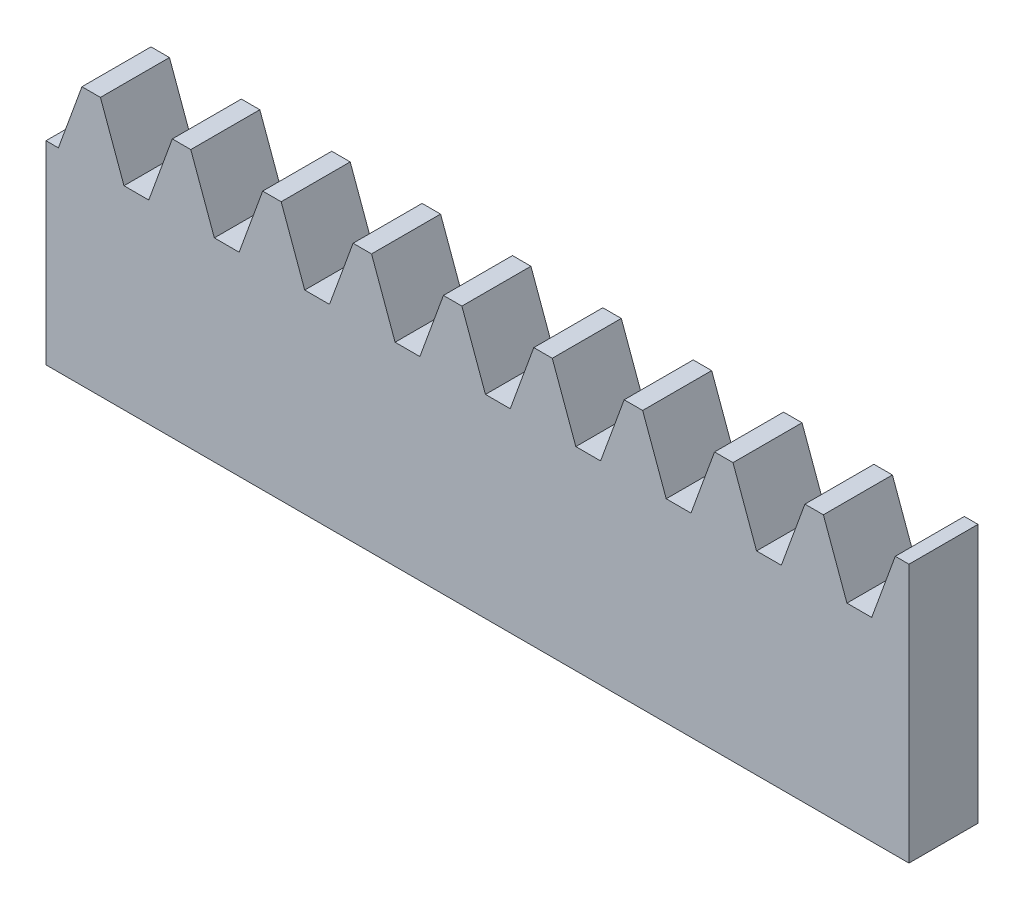
SolidWorks part; units mm, degrees
extrude "Blank" add sketch "BlankSke" against normal blind 12
sketch "BlankSke" plane through (0, 0, 0) normal (0, 0, 1) x (1, 0, 0)
  line L1 (0, 0) -> (150, 0)
  line L2 (0, 0) -> (0, 45)
  line L3 (0, 45) -> (150, 45)
  line L4 (150, 0) -> (150, 45)
  dimension "Length" = 150
  dimension "Blank_height" = 45
ref_plane "Plane1" through (0, 0, 0) normal (0, 0, 1) x (1, 0, 0)
ref_plane "Plane2" through (0, 0, 0) normal (0, 1, 0) x (1, 0, 0)
ref_plane "Plane3" through (0, 0, 0) normal (1, 0, 0) x (0, 0, -1)
other "Configuration Table"
sketch "HoldingSke" plane through (0, 0, 0) normal (0, 1, 0) x (1, 0, 0)
  line L0 (0, 0) -> (0.0278, 0.1981)
  line L1 (-15, 0) -> (100, 0) construction
  line L2 (0, 0) -> (-2.1039, 2.3779)
  line L3 (0, 0) -> (-11.863, 4.5341)
  line L4 (0, 0) -> (8.4773, 1.6478)
  line L5 (0, 0) -> (-23.7986, -8.8762)
  line L6 (0, 0) -> (-10.5278, -7.1032)
  line L9 (-71.009, 38.7566) -> (69.9449, 90.0596)
  line L10 (-76.2, 7.3779) -> (-36.2, 7.3779)
  line L11 (0, 0) -> (-12, 0)
  line L12 (-76.2, 101.6) -> (-76.033, 101.6)
  line L13 (24.9733, 27.94) -> (52.9518, 28.4284)
  line L14 (24.9733, 27.94) -> (24.9743, 27.94)
  line L15 (24.9733, 27.94) -> (100.4006, 29.5858)
  circle A0 centre (0, 0) radius 19.05
  circle A1 centre (0, 0) radius 20
  circle A2 centre (0, 0) radius 12.7
  dimension "MPH" = 40
  dimension "Diameter" = 38.1
  dimension "Num_teeth" = 11
  dimension "Pitch" = 0.2
  dimension "Show_teeth" = 998
  dimension "Thickness" = 12.7
  dimension "Ap" = 20
  dimension "Pitch_height" = 40
  dimension "Width" = 12
  dimension "Backlash" = 0.167
  dimension "Addendum_fac" = 1
  dimension "Dedendum_fac" = 1.25
  dimension "Clearance_fac" = 0.25
  dimension "Dedendum_add" = 0.001
  dimension "Length" = 150
  dimension "Module" = 5
sketch "TooCutSkeIll" plane through (0, 0, 0) normal (0, 0, 1) x (1, 0, 0)
  line L0 (-6.1999, 44.8684) -> (-2.4528, 34.5731)
  line L1 (-1.2772, 33.75) -> (1.2772, 33.75)
  line L2 (2.4528, 34.5731) -> (6.1999, 44.8684)
  line L3 (150, 45) -> (0, 45) construction
  line L4 (0, 0) -> (0, 64.897) construction
  line L5 (-13.208, 40) -> (12.954, 40) construction
  line L6 (0, 0) -> (150, 0) construction
  line L7 (4.428, 40) -> (4.428, 48.7463) construction
  line L8 (-4.428, 40) -> (-4.428, 48.7463) construction
  line L9 (6.3879, 45) -> (6.3879, 45.0254)
  line L10 (-6.3879, 45) -> (-6.3879, 45.0254)
  line L11 (-6.3879, 45.0254) -> (6.3879, 45.0254)
  arc A0 (1.2772, 33.75) -> (2.4528, 34.5731) centre (1.2772, 35.001) ccw
  arc A1 (-2.4528, 34.5731) -> (-1.2772, 33.75) centre (-1.2772, 35.001) ccw
  arc A2 (6.3879, 45) -> (6.1999, 44.8684) centre (6.3879, 44.8) ccw
  arc A3 (-6.1999, 44.8684) -> (-6.3879, 45) centre (-6.3879, 44.8) ccw
  dimension "Pitch_height" = 40
  dimension "Addendum_plus" = 5.0254
  dimension "Pressure_angle" = 20
  dimension "Gap_width" = 8.856
  dimension "Dedendum" = 6.25
extrude "ToothCutIll" [suppressed] cut sketch "TooCutSkeIll" against normal through all
sketch "TooCutSkeSim" plane through (0, 0, 0) normal (0, 0, 1) x (1, 0, 0)
  line L0 (2.1532, 33.75) -> (-2.1532, 33.75)
  line L1 (6.2571, 45.0254) -> (2.1532, 33.75)
  line L2 (0, 17.4625) -> (0, 53.467) construction
  line L3 (6.2571, 45.0254) -> (-6.2571, 45.0254)
  line L6 (-6.2571, 45.0254) -> (-2.1532, 33.75)
  line L9 (-4.428, 40) -> (4.428, 40) construction
  line L10 (0, 0) -> (150, 0) construction
  line L11 (4.428, 40) -> (4.428, 53.467) construction
  line L12 (-4.428, 40) -> (-4.428, 53.467) construction
  dimension "Pitch_height" = 40
  dimension "Addendum_plus" = 5.0254
  dimension "Pressure_angle" = 20
  dimension "Gap_width" = 8.856
  dimension "Dedendum" = 6.25
extrude "ToothCutSim" cut sketch "TooCutSkeSim" against normal through all
pattern_linear "TeethCuts" count 10 spacing 15.708 along (1, 0, 0) of "ToothCutIll", "ToothCutSim"
equation "' \"Module@HoldingSke\" = 6.35"
equation "' \"Num_teeth@HoldingSke\" = 12"
equation "' \"Ap@HoldingSke\" =  20"
equation "' \"Ap@HoldingSke\" = 20"
equation "' \"Width@HoldingSke\" = 0.25 * 25.4"
equation "' \"Show_teeth@HoldingSke\" = 500"
equation "' \"Backlash@HoldingSke\" = 0.009 * 25.4"
equation "' \"Addendum_fac@HoldingSke\" = 1.0"
equation "' \"Dedendum_fac@HoldingSke\" = 1.25"
equation "' \"Dedendum_add@HoldingSke\" = 0.00005 * 25.4"
equation "' \"Clearance_fac@HoldingSke\" = 0.25"
equation "' \"Pitch_height@HoldingSke\" = 1 * 25.4"
equation "' \"Length@HoldingSke\" = 4.71 * 25.4"
equation "\"Pitch@HoldingSke\" = 1 / \"Module@HoldingSke\""
equation "\"MPH@HoldingSke\" = \"Dedendum_fac@HoldingSke\" / \"Pitch@HoldingSke\" + 2 * \"Dedendum_add@HoldingSke\" + 0.002 * 25.4"
equation "\"MPH@HoldingSke\" = ((sgn( \"MPH@HoldingSke\" - \"Pitch_height@HoldingSke\")+1)*( \"MPH@HoldingSke\" - \"Pitch_height@HoldingSke\"))/2 + \"Pitch_height@HoldingSke\""
equation "\"Blank_height@BlankSke\" = \"Pitch_height@HoldingSke\" + \"Addendum_fac@HoldingSke\"  / \"Pitch@HoldingSke\" "
equation "\"Length@BlankSke\" =  \"Length@HoldingSke\""
equation "\"Face_width@Blank\" = \"Width@HoldingSke\""
equation "\"Pressure_angle@TooCutSkeIll\" = \"Ap@HoldingSke\""
equation "\"Addendum_plus@TooCutSkeIll\" =  \"Addendum_fac@HoldingSke\"  / \"Pitch@HoldingSke\" + 0.001 *25.4"
equation "\"Dedendum@TooCutSkeIll\" = \"Dedendum_fac@HoldingSke\"  / \"Pitch@HoldingSke\""
equation "\"Pitch_height@TooCutSkeIll\" =  \"MPH@HoldingSke\""
equation "\"Gap_width@TooCutSkeIll\" = 3.14159265 / 2 / \"Pitch@HoldingSke\" + 6 * \"Backlash@HoldingSke\""
equation "\"Pressure_angle@TooCutSkeSim\" = \"Ap@HoldingSke\""
equation "\"Addendum_plus@TooCutSkeSim\" =  \"Addendum_fac@HoldingSke\"  / \"Pitch@HoldingSke\" + 0.001 * 25.4"
equation "\"Dedendum@TooCutSkeSim\" = \"Dedendum_fac@HoldingSke\"  / \"Pitch@HoldingSke\""
equation "\"Pitch_height@TooCutSkeSim\" =  \"MPH@HoldingSke\""
equation "\"Gap_width@TooCutSkeSim\" = 3.14159265 / 2 / \"Pitch@HoldingSke\" + 6 * \"Backlash@HoldingSke\""
equation "\"Root_fillet@TooCutSkeIll\" = \"Clearance_fac@HoldingSke\" / \"Pitch@HoldingSke\" + \"Dedendum_add@HoldingSke\""
equation "\"Break_rad@TooCutSkeIll\" = 0.02 / \"Pitch@HoldingSke\" * 2"
equation "\"Linear_pitch@TeethCuts\" = 3.14159265 / \"Pitch@HoldingSke\""
equation "\"Num_teeth@HoldingSke\" = int( ( \"Length@HoldingSke\" + 0 ) / (3.14159265 / \"Pitch@HoldingSke\")) + 0.9999  + 1"
equation " \"Num_teeth@TeethCuts\" = int( \"Show_teeth@HoldingSke\" ) + 1"
equation " \"Num_teeth@TeethCuts\" = ((sgn( \"Num_teeth@TeethCuts\" - \"Num_teeth@HoldingSke\" )-1)*( \"Num_teeth@TeethCuts\" - \"Num_teeth@HoldingSke\" ))/-2+ \"Num_teeth@HoldingSke\""
equation " \"Num_teeth@TeethCuts\" = ((sgn( \"Num_teeth@TeethCuts\" - 2.0)+1)*( \"Num_teeth@TeethCuts\" - 2.0))/2 +2.0"
